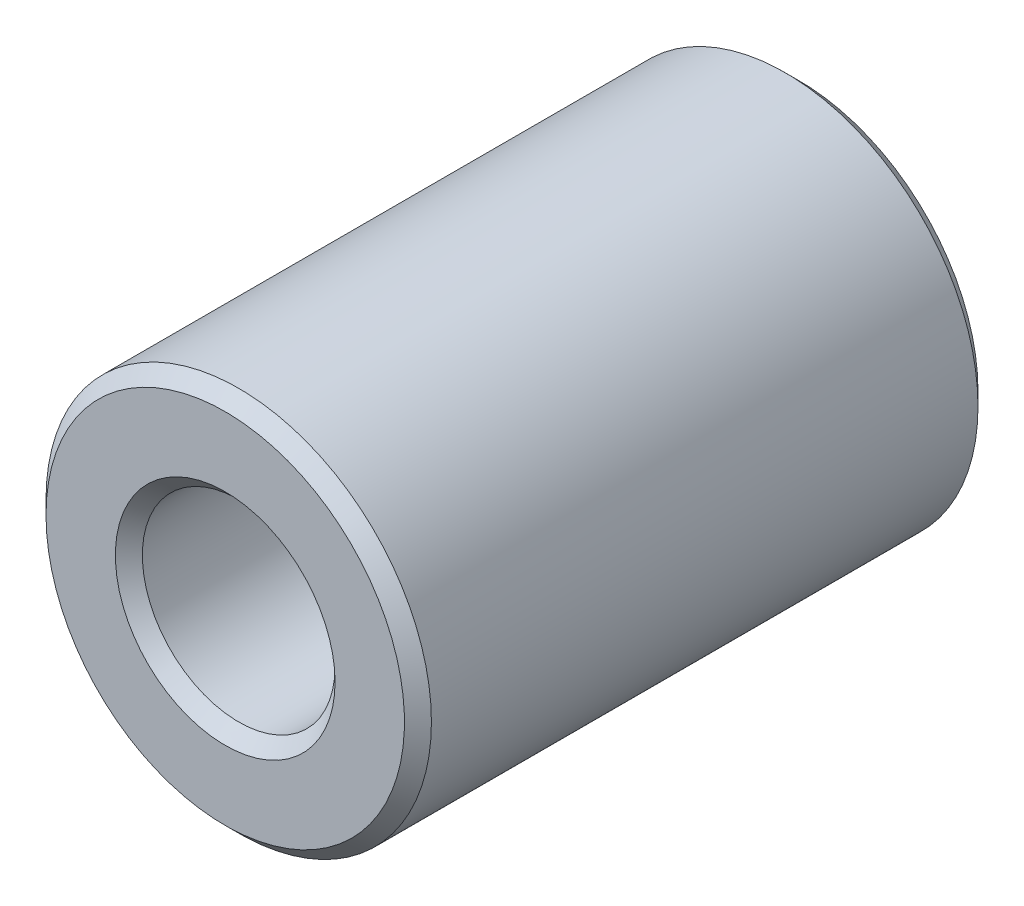
SolidWorks part; units mm, degrees
ref_plane "Front Plane" through (0, 0, 0) normal (0, 0, 1) x (1, 0, 0)
ref_plane "Top Plane" through (0, 0, 0) normal (0, 1, 0) x (1, 0, 0)
ref_plane "Right Plane" through (0, 0, 0) normal (1, 0, 0) x (0, 0, -1)
sketch "Sketch1" plane through (0, 0, 0) normal (0, 0, 1) x (1, 0, 0)
  line L0 (1.6002, 0) -> (3.2004, 0) construction
  circle A0 centre (0, 0) radius 1.6002 construction
  circle A1 centre (0, 0) radius 3.2004 construction
  circle A2 centre (0, 0) radius 3.175 construction
  circle A3 centre (0, 0) radius 1.5875 construction
  dimension "For Shaft Diameter" = 3.175
  dimension "For Housing ID" = 6.35
  dimension "OD" = 6.4008
  dimension "ID" = 3.2004
  dimension "D3" = 1.6002
sketch "Sketch13" plane through (0, 0, 0) normal (1, 0, 0) x (0, 0, -1)
  line L0 (4.7625, 0) -> (-4.7625, 0) construction
  line L1 (4.7625, 3.2004) -> (-4.7625, 3.2004) construction
  line L2 (0, 3.2004) -> (0, -3.2004) construction
  line L3 (0, 3.2004) -> (0, -3.2004) construction
  point P4 (0, 0)
  point P8 (0, 3.2004)
  dimension "Length" = 9.525
sketch "Sketch14" plane through (0, 0, 0) normal (0, 0, 1) x (1, 0, 0)
  circle A0 centre (0, 0) radius 1.6002 construction
  circle A1 centre (0, 0) radius 3.2004 construction
  circle A2 centre (0, 0) radius 1.6002
  circle A3 centre (0, 0) radius 3.2004
extrude "Boss-Extrude1" add sketch "Sketch14" against normal up to vertex (4.7625 mm away) and the other way up to vertex (4.7625 mm away) up to point (0, 3.2004, -4.7625) other way up to point (0, 3.2004, 4.7625)
chamfer "Chamfer1" distance 0.224 angle 45 4 edges at (3.2004, 0, -4.7625) (1.6002, 0, -4.7625) (1.6002, 0, 4.7625) (3.2004, 0, 4.7625)
equation "\"D1@Chamfer1\"=(\"OD@Sketch1\"-\"ID@Sketch1\")*.07"
